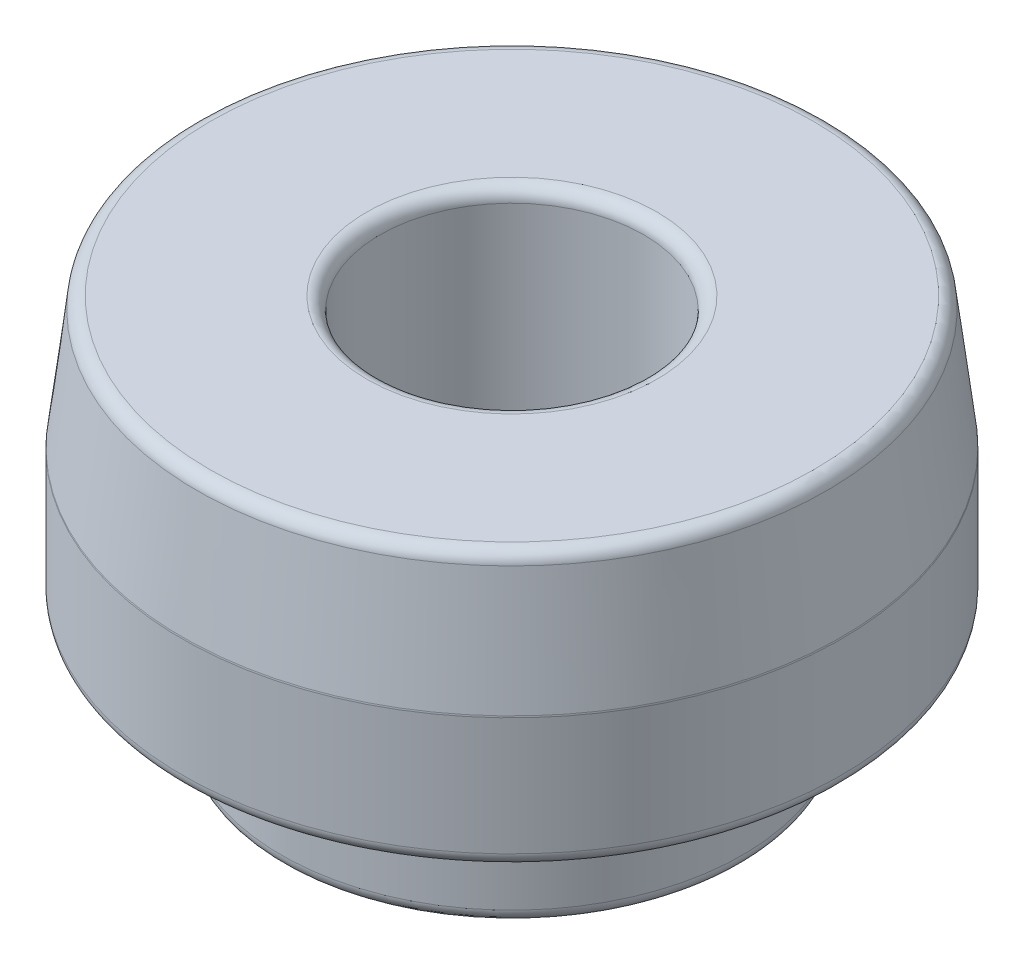
SolidWorks part; units mm, degrees
material "Ductile Iron"
ref_plane "Front Plane" through (0, 0, 0) normal (0, 0, 1) x (1, 0, 0)
ref_plane "Top Plane" through (0, 0, 0) normal (0, 1, 0) x (1, 0, 0)
ref_plane "Right Plane" through (0, 0, 0) normal (1, 0, 0) x (0, 0, -1)
sketch "Sketch1" plane through (0, 0, 0) normal (0, 0, 1) x (1, 0, 0)
  line L0 (0, 0) -> (0, 10) construction
  line L1 (5.5, 10) -> (11.4437, 10)
  line L2 (5, 0) -> (12.5, 0) construction
  line L3 (5, 0) -> (5, 10) construction
  line L4 (5, 10) -> (12.5, 10) construction
  line L5 (12.5, 0) -> (12.5, 10) construction
  line L6 (11.94, 9.5609) -> (12.4963, 5.0304)
  line L7 (12.5, 4.9694) -> (12.5, 0.5)
  line L8 (12, 0) -> (9.25, 0)
  line L9 (8.75, -0.5) -> (8.75, -4)
  line L10 (8.25, -4.5) -> (5.5, -4.5)
  line L11 (5, -4) -> (5, 9.5)
  arc A0 (5.5, -4.5) -> (5, -4) centre (5.5, -4) cw
  arc A1 (8.75, -4) -> (8.25, -4.5) centre (8.25, -4) cw
  arc A2 (9.25, 0) -> (8.75, -0.5) centre (9.25, -0.5) ccw
  arc A3 (12.5, 0.5) -> (12, 0) centre (12, 0.5) cw
  arc A4 (12.4963, 5.0304) -> (12.5, 4.9694) centre (12, 4.9694) cw
  arc A5 (11.4437, 10) -> (11.94, 9.5609) centre (11.4437, 9.5) cw
  arc A6 (5.5, 10) -> (5, 9.5) centre (5.5, 9.5) ccw
  point P16 (8.75, -4.5)
  point P19 (8.75, 0)
  point P25 (12.5, 5)
  point P28 (11.8861, 10)
  dimension "D6" = 0.5
  dimension "D1" = 10
  dimension "D2" = 7.5
  dimension "D3" = 5
  dimension "D4" = 4.5
  dimension "D5" = 97
revolve "Revolve1" add sketch "Sketch1" angle 360 about L0
